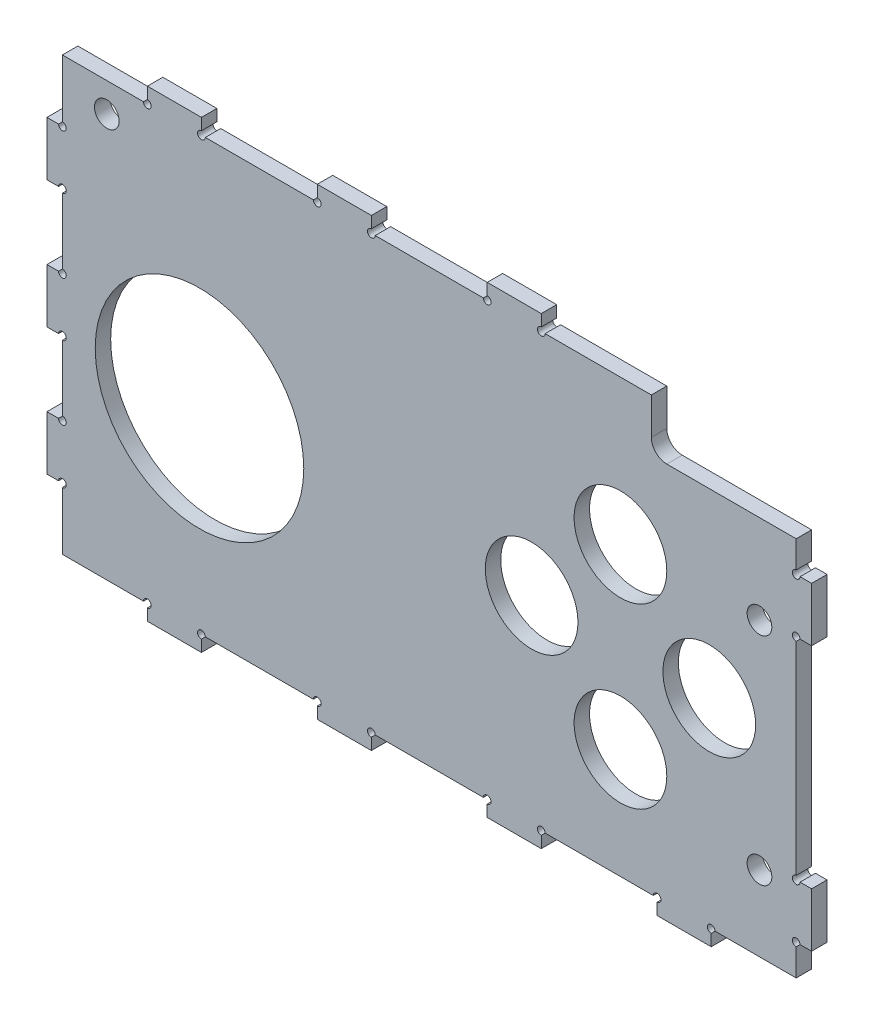
SolidWorks part; units mm, degrees
ref_plane "Front" through (0, 0, 0) normal (0, 0, 1) x (1, 0, 0)
ref_plane "Top" through (0, 0, 0) normal (0, 1, 0) x (1, 0, 0)
ref_plane "Right" through (0, 0, 0) normal (1, 0, 0) x (0, 0, -1)
sketch "草图2" plane through (0, 0, 0) normal (0, 0, 1) x (1, 0, 0)
  point P0 (67.5, 36)
  point P5 (67.5, 13)
  point P8 (56, 24.5)
  point P11 (79, 24.5)
  dimension "D4" = 11.5
sketch "草图3" plane through (0, 0, 0) normal (0, 0, 1) x (1, 0, 0)
  circle A0 centre (67.5, 36) radius 6
  circle A1 centre (56, 24.5) radius 6
  circle A2 centre (67.5, 13) radius 6
  circle A3 centre (79, 24.5) radius 6
  dimension "D1" = 12
sketch "草图4" plane through (0, 0, 0) normal (0, 0, 1) x (1, 0, 0)
  circle A0 centre (13, 24) radius 13.5
  circle A1 centre (56, 24.5) radius 6 construction
  dimension "D1" = 43
  dimension "D2" = 0.5
  dimension "D3" = 27
sketch "草图5" plane through (0, 0, 0) normal (0, 0, 1) x (1, 0, 0)
  line L1 (-4.75, 54.75) -> (90.25, 54.75)
  line L2 (-4.75, 54.75) -> (-4.75, -1.25)
  line L3 (-4.75, -1.25) -> (90.25, -1.25)
  line L4 (90.25, 54.75) -> (90.25, -1.25)
  circle A0 centre (13, 24) radius 13.5 construction
  dimension "D4" = 25.25
  dimension "D1" = 95
  dimension "D2" = 56
  dimension "D3" = 17.75
sketch "草图6" plane through (0, 0, 0) normal (0, 0, 1) x (1, 0, 0)
  line L1 (71.5, 57) -> (91.5, 57)
  line L2 (71.5, 57) -> (71.5, 48)
  line L3 (71.5, 48) -> (91.5, 48)
  line L4 (91.5, 57) -> (91.5, 48)
  circle A0 centre (67.5, 36) radius 6 construction
  dimension "D2" = 9
  dimension "17" = 20
  dimension "D3" = 12
  dimension "D4" = 4
extrude "凸台-拉伸1" add sketch "草图5" along normal blind 2
extrude "切除-拉伸2" cut sketch "草图3" along normal through all
extrude "切除-拉伸3" cut sketch "草图4" along normal through all
extrude "切除-拉伸4" cut sketch "草图6" along normal through all
fillet "圆角2" radius 2 1 edges at (71.5, 48, 1)
sketch "草图8" plane through (0, 0, 0) normal (0, 0, -1) x (-1, 0, 0)
  circle A0 centre (-85.5, 36.5) radius 1.6
  circle A1 centre (-85.5, 8.5) radius 1.6
  circle A2 centre (-1, 51) radius 1.6
extrude "切除-拉伸6" cut sketch "草图8" against normal through all
sketch "草图10" plane through (0, 0, 0) normal (0, 0, -1) x (-1, 0, 0)
  line L0 (-71.5, 54.75) -> (4.75, 54.75) construction
  line L1 (-13.25, 54.75) -> (-6.25, 54.75)
  line L2 (-13.25, 54.75) -> (-13.25, 56.75)
  line L3 (-13.25, 56.75) -> (-6.25, 56.75)
  line L4 (-6.25, 54.75) -> (-6.25, 56.75)
  line L5 (4.75, 54.75) -> (4.75, -1.25) construction
  line L6 (4.75, -1.25) -> (-90.25, -1.25) construction
  line L7 (-35.25, 54.75) -> (-28.25, 54.75)
  line L8 (-35.25, 54.75) -> (-35.25, 56.75)
  line L9 (-35.25, 56.75) -> (-28.25, 56.75)
  line L10 (-28.25, 54.75) -> (-28.25, 56.75)
  line L11 (-57.25, 54.75) -> (-50.25, 54.75)
  line L12 (-57.25, 54.75) -> (-57.25, 56.75)
  line L13 (-57.25, 56.75) -> (-50.25, 56.75)
  line L14 (-50.25, 54.75) -> (-50.25, 56.75)
  line L15 (-79.25, -1.25) -> (-72.25, -1.25)
  line L16 (-79.25, -1.25) -> (-79.25, -3.25)
  line L17 (-79.25, -3.25) -> (-72.25, -3.25)
  line L18 (-72.25, -1.25) -> (-72.25, -3.25)
  line L19 (-90.25, -1.25) -> (-90.25, 48) construction
  line L21 (-57.25, -1.25) -> (-50.25, -1.25)
  line L22 (-57.25, -1.25) -> (-57.25, -3.25)
  line L23 (-57.25, -3.25) -> (-50.25, -3.25)
  line L24 (-50.25, -1.25) -> (-50.25, -3.25)
  line L25 (-35.25, -1.25) -> (-28.25, -1.25)
  line L26 (-35.25, -1.25) -> (-35.25, -3.25)
  line L27 (-35.25, -3.25) -> (-28.25, -3.25)
  line L28 (-28.25, -1.25) -> (-28.25, -3.25)
  line L29 (-13.25, -1.25) -> (-6.25, -1.25)
  line L30 (-13.25, -1.25) -> (-13.25, -3.25)
  line L31 (-13.25, -3.25) -> (-6.25, -3.25)
  line L32 (-6.25, -1.25) -> (-6.25, -3.25)
  point P28 (-57.25, -2.25)
  dimension "D1" = 7
  dimension "D2" = 2
  dimension "D3" = 11
  dimension "D4" = 2
  dimension "D5" = 7
  dimension "D6" = 15
  dimension "D7" = 2
  dimension "D8" = 7
  dimension "D9" = 15
  dimension "D10" = 2
  dimension "D11" = 7
  dimension "D12" = 11
  dimension "D13" = 7
  dimension "D14" = 2
  dimension "D15" = 15
  dimension "D16" = 2
  dimension "D17" = 7
  dimension "D18" = 2
  dimension "D19" = 7
  dimension "D20" = 15
  dimension "D21" = 15
extrude "凸台-拉伸2" add sketch "草图10" against normal blind 2
sketch "草图11" plane through (0, 0, 0) normal (0, 0, -1) x (-1, 0, 0)
  circle A0 centre (-57.25, 54.75) radius 0.5
  circle A1 centre (-50.25, 54.75) radius 0.5
  circle A2 centre (-35.25, 54.75) radius 0.5
  circle A3 centre (-28.25, 54.75) radius 0.5
  circle A4 centre (-13.25, 54.75) radius 0.5
  circle A5 centre (-6.25, 54.75) radius 0.5
  circle A6 centre (-79.25, -1.25) radius 0.5
  circle A7 centre (-72.25, -1.25) radius 0.5
  circle A8 centre (-57.25, -1.25) radius 0.5
  circle A9 centre (-50.25, -1.25) radius 0.5
  circle A10 centre (-35.25, -1.25) radius 0.5
  circle A11 centre (-28.25, -1.25) radius 0.5
  circle A12 centre (-13.25, -1.25) radius 0.5
  circle A13 centre (-6.25, -1.25) radius 0.5
extrude "切除-拉伸8" cut sketch "草图11" against normal through all
sketch "草图12" plane through (0, 0, 2) normal (0, 0, 1) x (1, 0, 0)
  line L0 (90.25, -1.25) -> (90.25, 48) construction
  line L1 (90.25, 44) -> (92.25, 44)
  line L2 (90.25, 44) -> (90.25, 37)
  line L3 (90.25, 37) -> (92.25, 37)
  line L4 (92.25, 44) -> (92.25, 37)
  line L5 (73.5, 48) -> (90.25, 48) construction
  line L6 (79.75, -1.25) -> (90.25, -1.25) construction
  line L7 (90.25, 2.75) -> (92.25, 2.75)
  line L8 (90.25, 2.75) -> (90.25, 9.75)
  line L9 (90.25, 9.75) -> (92.25, 9.75)
  line L10 (92.25, 2.75) -> (92.25, 9.75)
  dimension "D1" = 2
  dimension "D2" = 7
  dimension "D3" = 4
  dimension "D4" = 2
  dimension "D5" = 7
  dimension "D6" = 4
extrude "凸台-拉伸3" add sketch "草图12" against normal blind 2
sketch "草图13" plane through (0, 0, 2) normal (0, 0, 1) x (1, 0, 0)
  line L0 (-4.75, 54.75) -> (-4.75, -1.25) construction
  line L1 (-4.75, 6.75) -> (-6.75, 6.75)
  line L2 (-4.75, 6.75) -> (-4.75, 13.75)
  line L3 (-4.75, 13.75) -> (-6.75, 13.75)
  line L4 (-6.75, 6.75) -> (-6.75, 13.75)
  line L5 (-4.75, -1.25) -> (5.75, -1.25) construction
  line L6 (5.75, 54.75) -> (-4.75, 54.75) construction
  line L7 (-4.75, 30.25) -> (-6.75, 30.25)
  line L8 (-4.75, 30.25) -> (-4.75, 23.25)
  line L9 (-4.75, 23.25) -> (-6.75, 23.25)
  line L10 (-6.75, 30.25) -> (-6.75, 23.25)
  line L11 (-4.75, 46.75) -> (-6.75, 46.75)
  line L12 (-4.75, 46.75) -> (-4.75, 39.75)
  line L13 (-4.75, 39.75) -> (-6.75, 39.75)
  line L14 (-6.75, 46.75) -> (-6.75, 39.75)
  point P18 (-5.75, 30.25)
  dimension "D1" = 2
  dimension "D2" = 7
  dimension "D3" = 8
  dimension "D4" = 2
  dimension "D5" = 7
  dimension "D6" = 2
  dimension "D7" = 7
  dimension "D8" = 8
  dimension "D9" = 9.5
extrude "凸台-拉伸4" add sketch "草图13" against normal blind 2
sketch "草图14" plane through (0, 0, 2) normal (0, 0, 1) x (1, 0, 0)
  circle A0 centre (-4.75, 46.75) radius 0.5
  circle A1 centre (-4.75, 39.75) radius 0.5
  circle A2 centre (-4.75, 30.25) radius 0.5
  circle A3 centre (-4.75, 23.25) radius 0.5
  circle A4 centre (-4.75, 13.75) radius 0.5
  circle A5 centre (-4.75, 6.75) radius 0.5
  circle A6 centre (90.25, 44) radius 0.5
  circle A7 centre (90.25, 37) radius 0.5
  circle A8 centre (90.25, 9.75) radius 0.5
  circle A9 centre (90.25, 2.75) radius 0.5
extrude "切除-拉伸9" cut sketch "草图14" against normal through all
